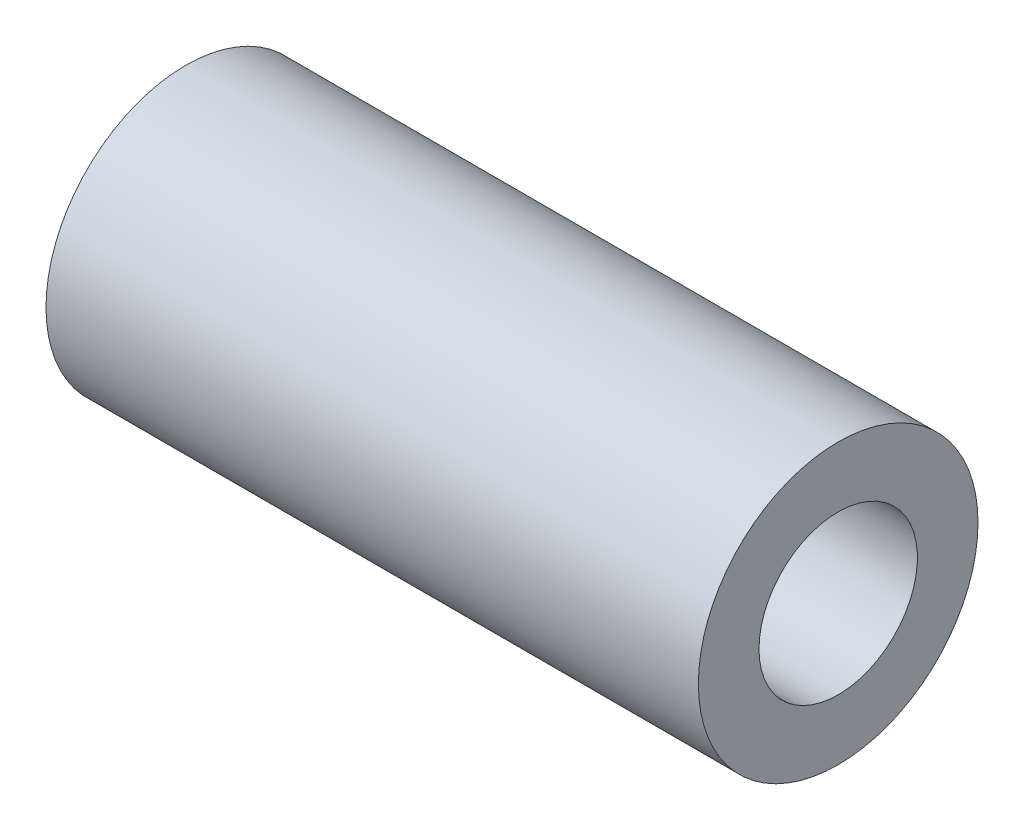
SolidWorks part; units mm, degrees
ref_plane "Front Plane" through (0, 0, 0) normal (0, 0, 1) x (1, 0, 0)
ref_plane "Top Plane" through (0, 0, 0) normal (0, 1, 0) x (1, 0, 0)
ref_plane "Right Plane" through (0, 0, 0) normal (1, 0, 0) x (0, 0, -1)
sketch "Axial blank profile" plane through (0, 0, 0) normal (0, 0, 1) x (1, 0, 0)
  line L0 (-60, 0) -> (30, 0) construction
  line L1 (-17, 1.7) -> (-3, 1.7)
  line L2 (-3, 1.7) -> (-3, 3)
  line L3 (-3, 3) -> (-17, 3)
  line L4 (-17, 3) -> (-17, 1.7)
revolve "Native revolved blank" add sketch "Axial blank profile" angle 360 about L0
